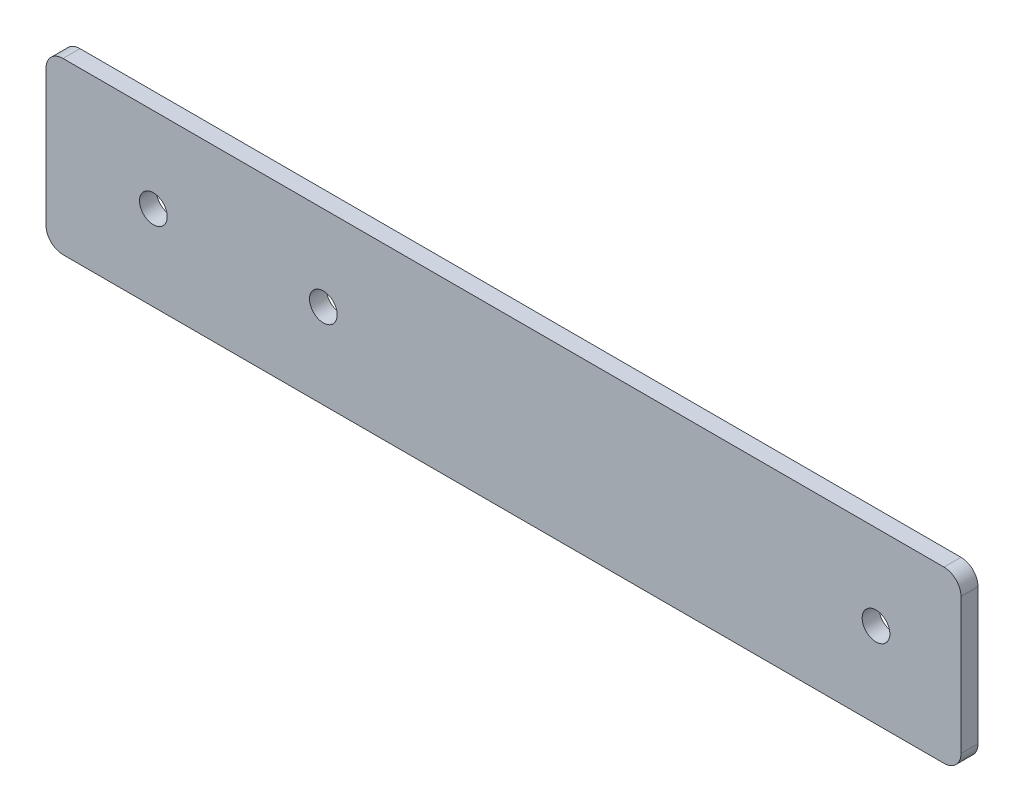
SolidWorks part; units mm, degrees
ref_plane "Front" through (0, 0, 0) normal (0, 0, 1) x (1, 0, 0)
ref_plane "Top" through (0, 0, 0) normal (0, 1, 0) x (1, 0, 0)
ref_plane "Right" through (0, 0, 0) normal (1, 0, 0) x (0, 0, -1)
sketch "Sketch1" plane through (0, 0, 0) normal (0, 0, 1) x (1, 0, 0)
  line L9 (17.7896, 202.3011) -> (17.7896, 176.9011)
  line L10 (17.7896, 176.9011) -> (-118.9384, 176.9011)
  line L11 (-118.9384, 176.9011) -> (-118.9384, 202.3011)
  line L13 (-118.9384, 202.3011) -> (17.7896, 202.3011)
  circle A0 centre (5.0896, 189.6011) radius 2.0701
  arc A1 (5.1658, 187.5324) -> (5.1658, 191.6698) centre (5.0896, 189.6011) ccw construction
  circle A2 centre (-77.4929, 189.6011) radius 2.0701
  circle A3 centre (-102.8929, 189.6011) radius 2.0701
  arc A4 (-100.8242, 189.6773) -> (-104.9616, 189.6773) centre (-102.8929, 189.6011) ccw construction
  arc A5 (-75.4242, 189.6773) -> (-79.5616, 189.6773) centre (-77.4929, 189.6011) ccw construction
  point P0 (0, 0)
  point P1 (0, 0)
  dimension "D1" = 25.4
extrude "Boss-Extrude1" add sketch "Sketch1" along normal blind 2.54
fillet "Fillet1" radius 2.54 4 edges at (17.7896, 202.3011, 1.27) (17.7896, 176.9011, 1.27) (-118.9384, 176.9011, 1.27) (-118.9384, 202.3011, 1.27)
sketch "Bend-Lines1" [suppressed] plane through (0, 0, 0) normal (0, 1, 0) x (1, 0, 0)
sketch "Bounding-Box1" [suppressed] plane through (0, 0, 0) normal (0, 1, 0) x (1, 0, 0)
